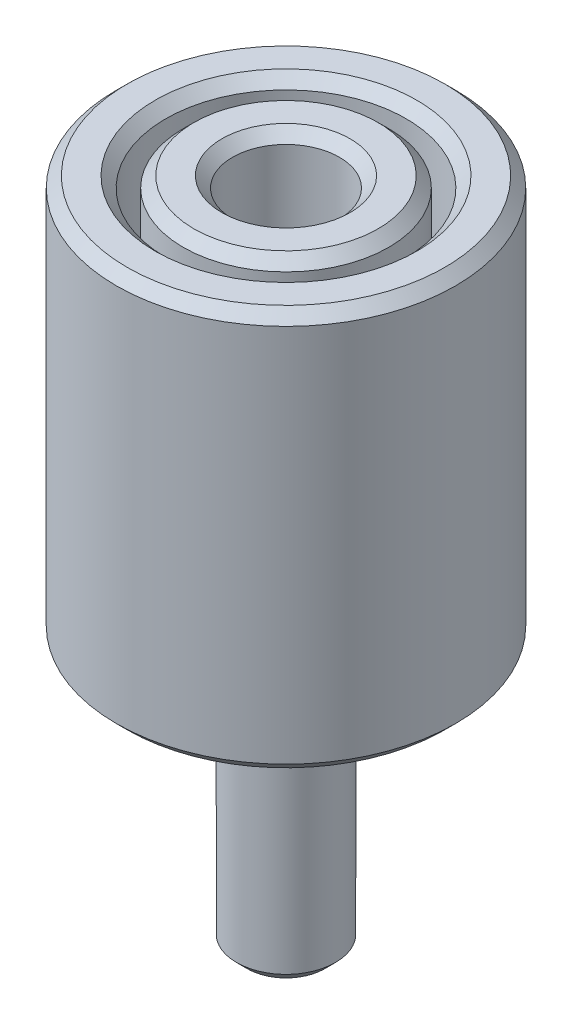
SolidWorks part; units mm, degrees
ref_plane "Спереди" through (0, 0, 0) normal (0, 0, 1) x (1, 0, 0)
ref_plane "Сверху" through (0, 0, 0) normal (0, 1, 0) x (1, 0, 0)
ref_plane "Справа" through (0, 0, 0) normal (1, 0, 0) x (0, 0, -1)
sketch "Эскиз1" plane through (0, 0, 0) normal (0, 0, 1) x (1, 0, 0)
  line L18 (-6.35, 25) -> (-6.35, 10)
  line L19 (-6.35, 10) -> (-2.5, 10)
  line L20 (-2.5, 10) -> (-2.5, 9)
  line L21 (-2.5, 9) -> (-1.85, 9)
  line L22 (-1.85, 9) -> (-1.85, 0)
  line L23 (-1.85, 0) -> (0, 0)
  line L24 (-6.35, 25) -> (-4.5, 25)
  line L25 (-4.5, 25) -> (-4.5, 11.4996)
  line L26 (-4.5, 11.4996) -> (-3.85, 11.4996)
  line L27 (-3.85, 11.4996) -> (-3.85, 25)
  line L28 (-3.85, 25) -> (-2, 25)
  line L29 (-2, 25) -> (-2, 11.4996)
  line L30 (-2, 11.4996) -> (0, 11.4996)
  line L31 (0, 11.4996) -> (0, 0)
  dimension "D1" = 15
  dimension "D2" = 4.5
  dimension "D3" = 9
  dimension "D4" = 10
  dimension "D5" = 3.85
  dimension "D6" = 2
revolve "Повернуть1" add sketch "Эскиз1" angle 360 about L31
chamfer "Фаска2" distance 0.4 angle 45 6 edges at (0, 25, 2) (0, 25, 3.85) (0, 25, 4.5) (0, 25, 6.35) (0, 10, 6.35) (0, 0, 1.85)
